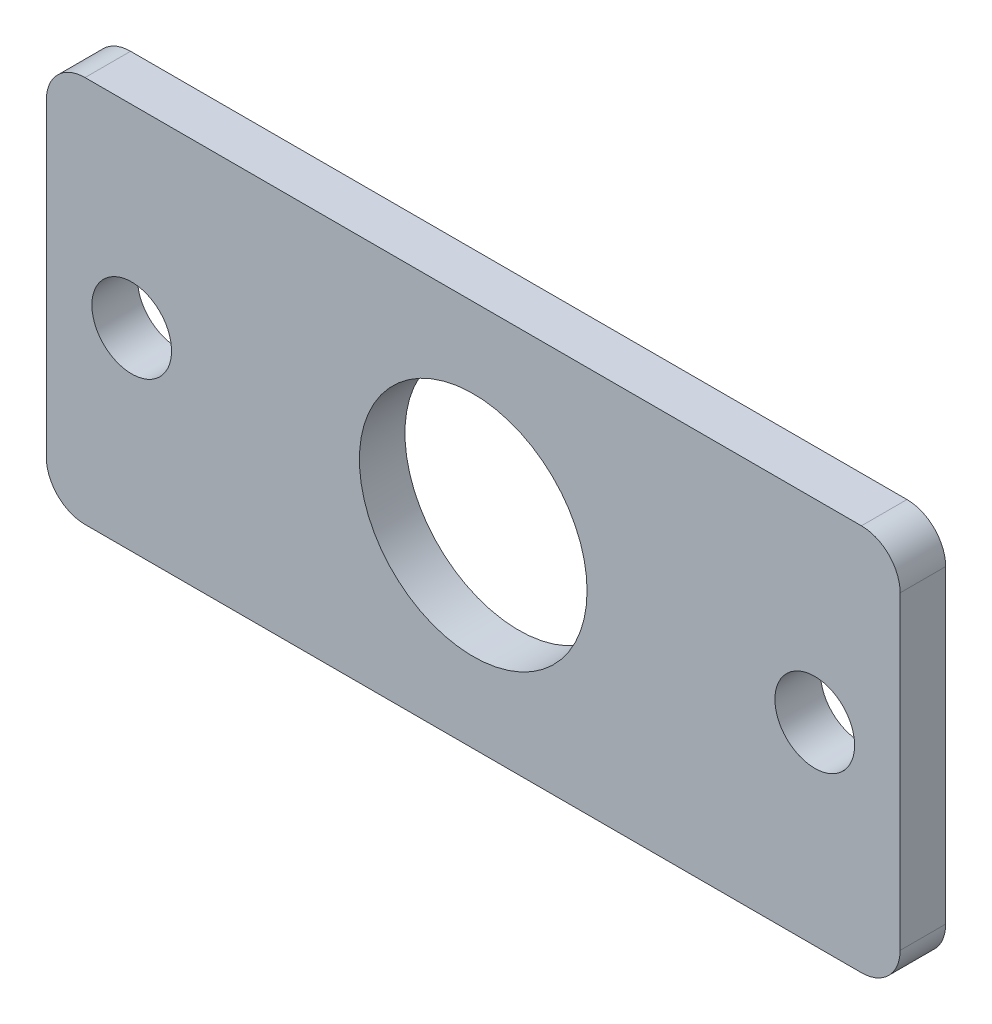
SolidWorks part; units mm, degrees
ref_plane "前视基准面" through (0, 0, 0) normal (0, 0, 1) x (1, 0, 0)
ref_plane "上视基准面" through (0, 0, 0) normal (0, 1, 0) x (1, 0, 0)
ref_plane "右视基准面" through (0, 0, 0) normal (1, 0, 0) x (0, 0, -1)
sketch "草图1" plane through (0, 0, 0) normal (0, 0, 1) x (1, 0, 0)
  line L0 (-30, 0) -> (30, 0) construction
  line L1 (37.5, -17) -> (-37.5, -17)
  line L2 (37.5, -17) -> (37.5, 17)
  line L3 (37.5, 17) -> (-37.5, 17)
  line L4 (-37.5, -17) -> (-37.5, 17)
  line L5 (37.5, -17) -> (-37.5, 17) construction
  line L6 (37.5, 17) -> (-37.5, -17) construction
  line L7 (0, 0) -> (0, 17) construction
  line L8 (0, 0) -> (0, -4) construction
  circle A0 centre (30, 0) radius 3.5
  circle A1 centre (0, 0) radius 10
  point P0 (0, 0)
  point P10 (30, 10)
  dimension "DD" = 7
  dimension "L" = 20
  dimension "BB" = 75
  dimension "BC" = 34
  dimension "AA" = 60
  dimension "BG" = 20
  dimension "BF" = 4
sketch "草图3" plane through (0, 0, 0) normal (0, 0, 1) x (1, 0, 0)
  line L0 (37.5, -17) -> (-37.5, -17) construction
  line L1 (-37.5, -17) -> (-37.5, 17) construction
  line L2 (37.5, 17) -> (-37.5, 17) construction
  line L3 (37.5, -17) -> (37.5, 17) construction
  line L4 (37.5, -17) -> (-37.5, -17)
  line L5 (-37.5, -17) -> (-37.5, 17)
  line L6 (37.5, 17) -> (-37.5, 17)
  line L7 (37.5, -17) -> (37.5, 17)
extrude "凸台-拉伸1" add sketch "草图3" along normal blind 4
sketch "草图6" plane through (0, 0, 4) normal (0, 0, 1) x (1, 0, 0)
  circle A0 centre (0, 0) radius 10 construction
  circle A1 centre (0, 0) radius 10
extrude "切除-拉伸2" cut sketch "草图6" against normal through all
fillet "圆角1" radius 3.4 4 edges at (37.5, 17, 2) (37.5, -17, 2) (-37.5, -17, 2) (-37.5, 17, 2)
sketch "草图4" plane through (0, 0, 4) normal (0, 0, 1) x (1, 0, 0)
  line L0 (0, 0) -> (0, 17) construction
  circle A1 centre (30, 0) radius 3.5 construction
  circle A3 centre (30, 0) radius 3.5
  circle A4 centre (-30, 0) radius 3.5
extrude "20" cut sketch "草图4" against normal through all
sketch "草图5" [suppressed] plane through (0, 0, 4) normal (0, 0, 1) x (1, 0, 0)
  line L0 (0, 0) -> (-30, 0) construction
  line L1 (0, 0) -> (0, 17) construction
  circle A2 centre (30, 10) radius 3.5
  circle A3 centre (30, 0) radius 3.5 construction
  circle A4 centre (-30, 10) radius 3.5
  circle A5 centre (30, -10) radius 3.5
  circle A6 centre (-30, -10) radius 3.5
extrude "40" [suppressed] cut sketch "草图5" against normal through all
equation "\"D1@凸台-拉伸1\" = \"BF@草图1\""
equation "\"D1@圆角1\" = \"BC@草图1\"*0.1"
